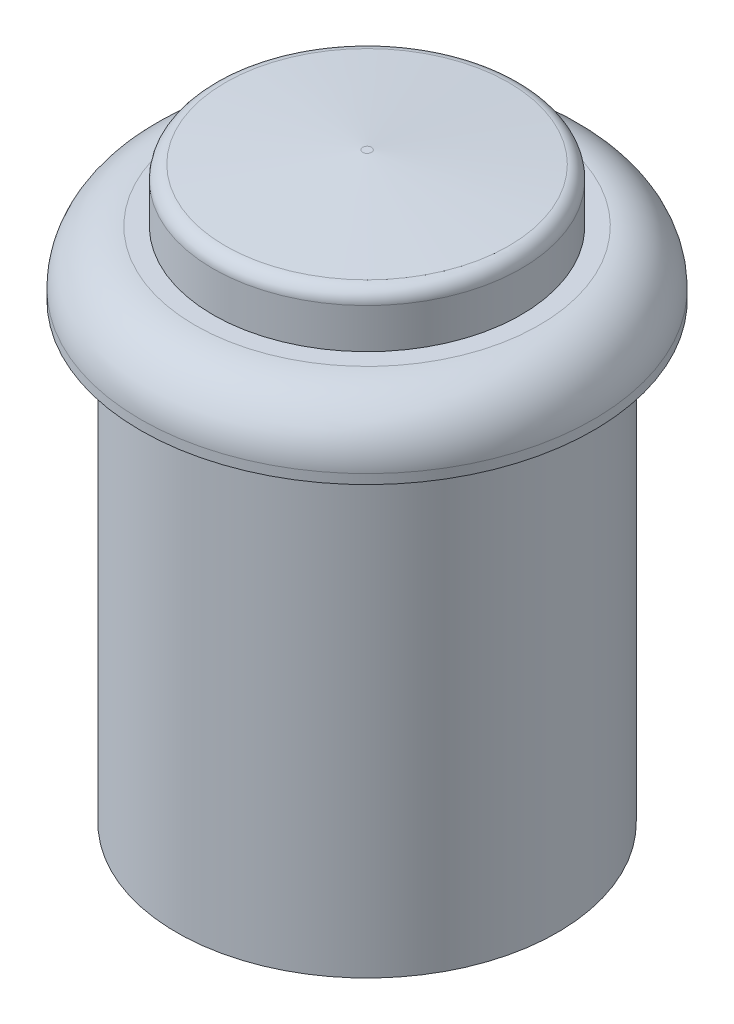
SolidWorks part; units mm, degrees
ref_plane "Front Plane" through (0, 0, 0) normal (0, 0, 1) x (1, 0, 0)
ref_plane "Top Plane" through (0, 0, 0) normal (0, 1, 0) x (1, 0, 0)
ref_plane "Right Plane" through (0, 0, 0) normal (1, 0, 0) x (0, 0, -1)
sketch "Sketch1" plane through (0, 0, 0) normal (0, 1, 0) x (1, 0, 0)
  circle A0 centre (0, 0) radius 16.65
  dimension "D1" = 33.3
extrude "Boss-Extrude1" add sketch "Sketch1" along normal blind 4.7
sketch "Sketch2" plane through (0, 4.7, 0) normal (0, 1, 0) x (1, 0, 0)
  circle A0 centre (0, 0) radius 11.325
  dimension "D1" = 22.65
extrude "Boss-Extrude2" add sketch "Sketch2" along normal blind 4.85
sketch "Sketch3" plane through (0, 0, 0) normal (0, -1, 0) x (1, 0, 0)
  circle A0 centre (0, 0) radius 14
  dimension "D1" = 28
extrude "Boss-Extrude3" add sketch "Sketch3" along normal blind 33.3
fillet "Fillet1" radius 4 1 edges at (0, 4.7, 16.65)
chamfer "Chamfer1" distance 1 distance2 11 1 edges at (0, 9.55, 11.325)
fillet "Fillet2" radius 1 1 edges at (0, 8.55, 11.325)
